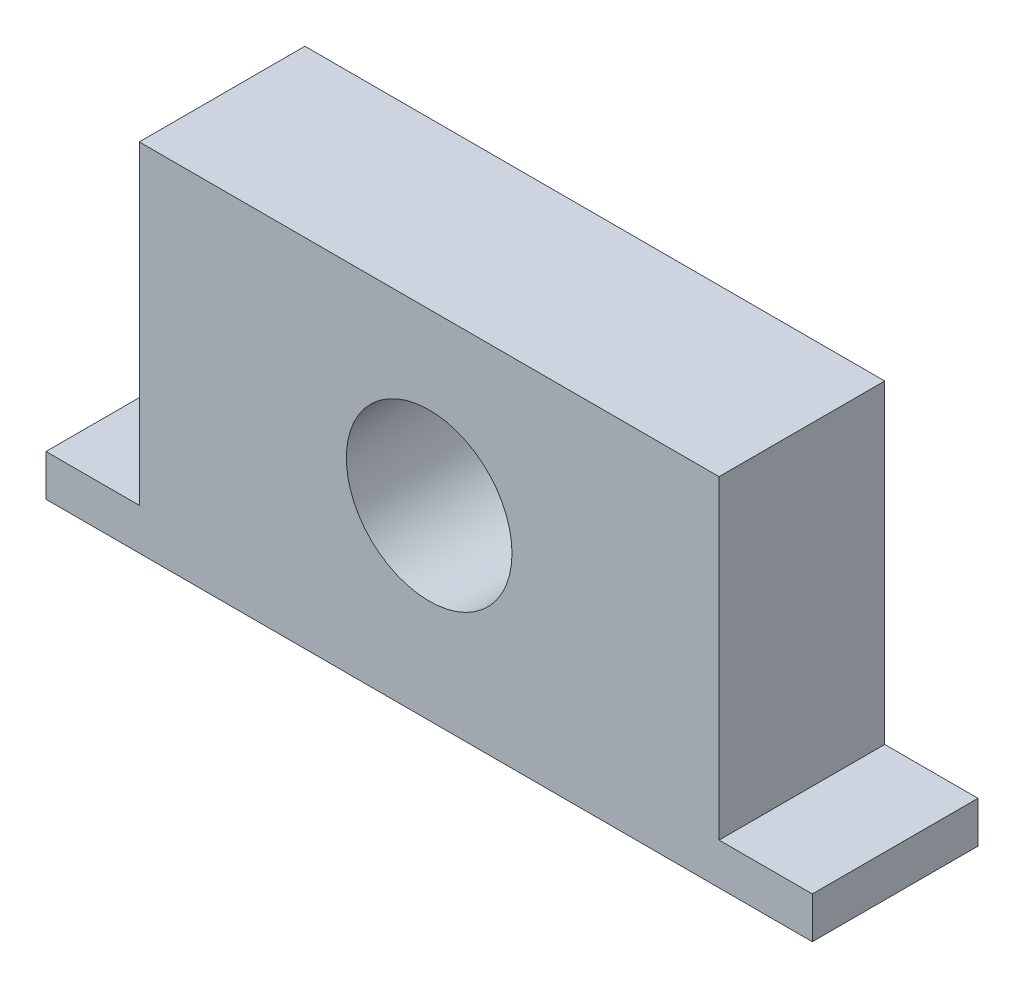
SolidWorks part; units mm, degrees
ref_plane "Front Plane" through (0, 0, 0) normal (0, 0, 1) x (1, 0, 0)
ref_plane "Top Plane" through (0, 0, 0) normal (0, 1, 0) x (1, 0, 0)
ref_plane "Right Plane" through (0, 0, 0) normal (1, 0, 0) x (0, 0, -1)
sketch "Sketch1" plane through (0, 0, 0) normal (0, 1, 0) x (1, 0, 0)
  line L1 (0, 0) -> (58.7502, 0)
  line L2 (0, 0) -> (0, 12.7)
  line L3 (0, 12.7) -> (58.7502, 12.7)
  line L4 (58.7502, 0) -> (58.7502, 12.7)
  dimension "D1" = 58.7502
  dimension "D2" = 12.7
extrude "Boss-Extrude1" add sketch "Sketch1" along normal blind 3.175
sketch "Sketch2" plane through (0, 3.175, 0) normal (0, 1, 0) x (1, 0, 0)
  line L0 (0, 0) -> (58.7502, 0) construction
  line L1 (7.1501, 0) -> (51.6001, 0)
  line L2 (7.1501, 0) -> (7.1501, 12.7)
  line L3 (7.1501, 12.7) -> (51.6001, 12.7)
  line L4 (51.6001, 0) -> (51.6001, 12.7)
  line L5 (58.7502, 12.7) -> (0, 12.7) construction
  line L6 (58.7502, 0) -> (58.7502, 12.7) construction
  dimension "D1" = 44.45
  dimension "D2" = 7.1501
extrude "Boss-Extrude2" add sketch "Sketch2" along normal blind 24.13
sketch "Sketch3" plane through (0, 0, 0) normal (0, 0, 1) x (1, 0, 0)
  line L0 (0, 0) -> (58.7502, 0) construction
  line L1 (7.1501, 27.305) -> (7.1501, 3.175) construction
  circle A0 centre (29.3751, 14.2748) radius 6.35
  dimension "D3" = 12.7
  dimension "D1" = 14.2748
  dimension "D2" = 22.225
extrude "Cut-Extrude1" cut sketch "Sketch3" against normal blind 24.13
